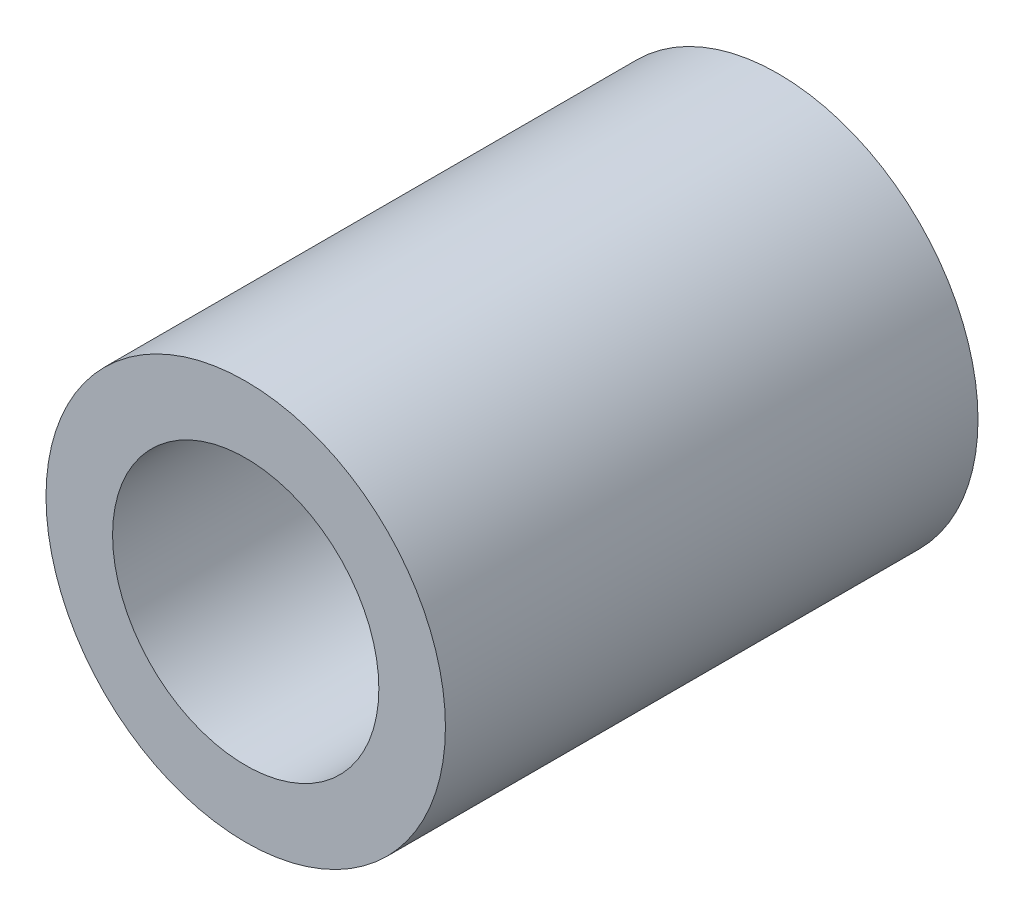
SolidWorks part; units mm, degrees
ref_plane "Plan1" through (0, 0, 0) normal (0, 0, 1) x (1, 0, 0)
ref_plane "Plan2" through (0, 0, 0) normal (0, 1, 0) x (1, 0, 0)
ref_plane "Plan3" through (0, 0, 0) normal (1, 0, 0) x (0, 0, -1)
sketch "Esquisse1" plane through (0, 0, 0) normal (0, 0, 1) x (1, 0, 0)
  circle A0 centre (0, 0) radius 12
  circle A1 centre (0, 0) radius 8
  dimension "D1" = 24
  dimension "D2" = 16
extrude "Base-Extrusion" add sketch "Esquisse1" along normal blind 32
